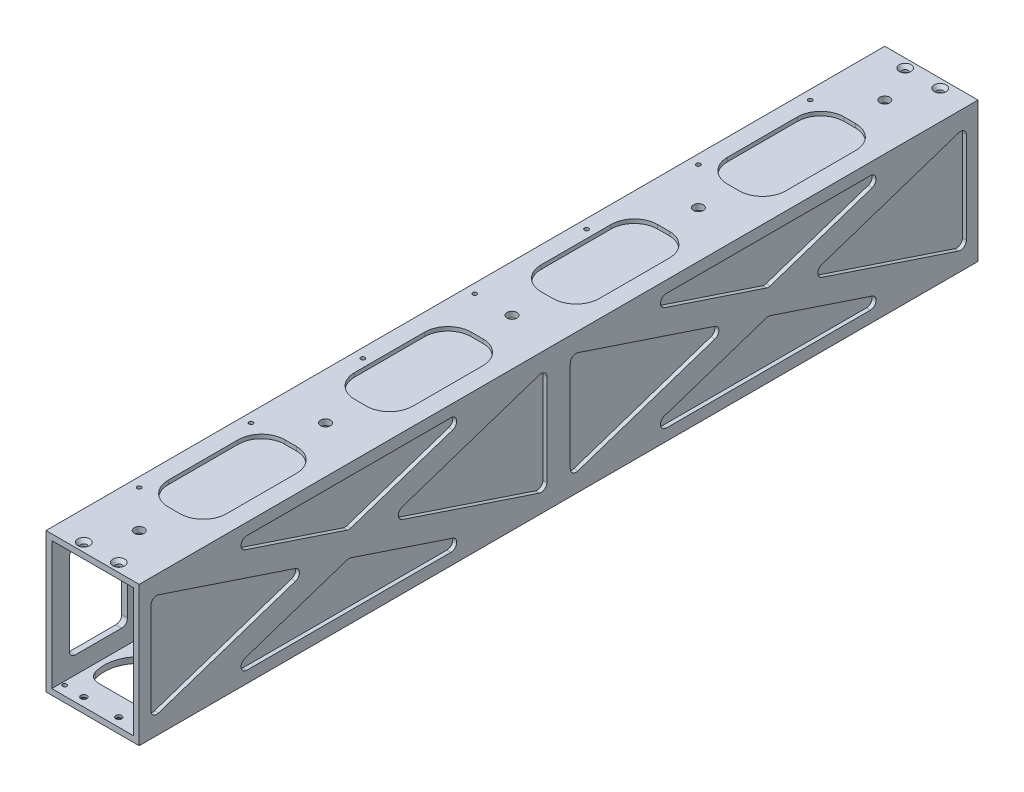
SolidWorks part; units mm, degrees
material "6061-T6 (SS)"
ref_plane "Front Plane" through (0, 0, 0) normal (0, 0, 1) x (1, 0, 0)
ref_plane "Top Plane" through (0, 0, 0) normal (0, 1, 0) x (1, 0, 0)
ref_plane "Right Plane" through (0, 0, 0) normal (1, 0, 0) x (0, 0, -1)
sketch "Sketch1" plane through (0, 0, 0) normal (0, 0, 1) x (1, 0, 0)
  line L0 (3.175, 3.175) -> (3.175, 73.025)
  line L1 (0, 0) -> (50.8, 0)
  line L2 (0, 0) -> (0, 76.2)
  line L3 (0, 76.2) -> (50.8, 76.2)
  line L4 (50.8, 0) -> (50.8, 76.2)
  line L5 (3.175, 73.025) -> (47.625, 73.025)
  line L6 (47.625, 3.175) -> (47.625, 73.025)
  line L7 (3.175, 3.175) -> (47.625, 3.175)
  dimension "D1" = 76.2
  dimension "D2" = 50.8
  dimension "D3" = 3.175
extrude "Boss-Extrude1" add sketch "Sketch1" along normal blind 457.2
sketch "Sketch2" plane through (50.8, 0, 0) normal (1, 0, 0) x (0, 0, -1)
  line L0 (-457.2, 76.2) -> (-228.6, 0) construction
  line L1 (-457.2, 0) -> (0, 0) construction
  line L2 (-228.6, 0) -> (-228.6, 76.2) construction
  line L3 (-457.2, 76.2) -> (0, 76.2) construction
  line L4 (-228.6, 76.2) -> (0, 0) construction
  line L5 (-457.2, 0) -> (-228.6, 76.2) construction
  line L6 (0, 76.2) -> (-228.6, 0) construction
  line L7 (-222.25, 62.9848) -> (-222.25, 13.2152)
  line L8 (-399.5083, 63.6629) -> (-343.904, 45.1282)
  line L9 (-459.208, 70.1759) -> (-230.608, -6.0241) construction
  line L10 (-455.192, 82.2241) -> (-226.592, 6.0241) construction
  line L11 (-446.671, 65.9968) -> (-372.0167, 41.1121)
  line L12 (-459.208, 6.0241) -> (-230.608, 82.2241) construction
  line L13 (-226.592, 82.2241) -> (2.008, 6.0241) construction
  line L14 (-455.192, -6.0241) -> (-226.592, 70.1759) construction
  line L15 (-234.95, 62.9848) -> (-234.95, 13.2152)
  line L16 (-57.6917, 63.6629) -> (-113.296, 45.1282)
  line L17 (-10.529, 65.9968) -> (-85.1833, 41.1121)
  line L18 (-170.9083, 63.6629) -> (-115.304, 45.1282)
  line L19 (-218.071, 65.9968) -> (-143.4167, 41.1121)
  line L20 (-6.35, 6.35) -> (-6.35, 69.85)
  line L21 (-6.35, 69.85) -> (-450.85, 69.85)
  line L22 (-450.85, 69.85) -> (-450.85, 6.35)
  line L23 (-450.85, 6.35) -> (-6.35, 6.35)
  line L24 (-6.35, 13.2152) -> (-6.35, 62.9848)
  line L25 (-287.2957, 69.85) -> (-398.5043, 69.85)
  line L26 (-450.85, 62.9848) -> (-450.85, 13.2152)
  line L27 (-398.5043, 6.35) -> (-287.2957, 6.35)
  line L28 (-446.671, 10.2032) -> (-372.0167, 35.0879)
  line L29 (-399.5083, 12.5371) -> (-343.904, 31.0718)
  line L30 (-341.896, 45.1282) -> (-286.2917, 63.6629)
  line L31 (-313.7833, 41.1121) -> (-239.129, 65.9968)
  line L32 (-230.608, 70.1759) -> (-2.008, -6.0241) construction
  line L33 (-341.896, 31.0718) -> (-286.2917, 12.5371)
  line L34 (2.008, 70.1759) -> (-226.592, -6.0241) construction
  line L35 (-2.008, 82.2241) -> (-230.608, 6.0241) construction
  line L36 (-313.7833, 35.0879) -> (-239.129, 10.2032)
  line L37 (-143.4167, 35.0879) -> (-218.071, 10.2032)
  line L38 (-113.296, 31.0718) -> (-57.6917, 12.5371)
  line L39 (-85.1833, 35.0879) -> (-10.529, 10.2032)
  line L40 (-115.304, 31.0718) -> (-170.9083, 12.5371)
  line L41 (-169.9043, 69.85) -> (-58.6957, 69.85)
  line L42 (-169.9043, 6.35) -> (-58.6957, 6.35)
  arc A0 (-85.1833, 35.0879) -> (-85.1833, 41.1121) centre (-84.1793, 38.1) cw
  arc A1 (-113.296, 45.1282) -> (-115.304, 45.1282) centre (-114.3, 48.1402) cw
  arc A2 (-218.071, 10.2032) -> (-222.25, 13.2152) centre (-219.075, 13.2152) cw
  arc A3 (-222.25, 62.9848) -> (-218.071, 65.9968) centre (-219.075, 62.9848) cw
  arc A4 (-287.2957, 6.35) -> (-286.2917, 12.5371) centre (-287.2957, 9.525) ccw
  arc A5 (-398.5043, 6.35) -> (-399.5083, 12.5371) centre (-398.5043, 9.525) cw
  arc A6 (-341.896, 31.0718) -> (-343.904, 31.0718) centre (-342.9, 28.0598) ccw
  arc A7 (-239.129, 10.2032) -> (-234.95, 13.2152) centre (-238.125, 13.2152) ccw
  arc A8 (-234.95, 62.9848) -> (-239.129, 65.9968) centre (-238.125, 62.9848) ccw
  arc A9 (-313.7833, 35.0879) -> (-313.7833, 41.1121) centre (-312.7793, 38.1) cw
  arc A10 (-286.2917, 63.6629) -> (-287.2957, 69.85) centre (-287.2957, 66.675) ccw
  arc A11 (-398.5043, 69.85) -> (-399.5083, 63.6629) centre (-398.5043, 66.675) ccw
  arc A12 (-341.896, 45.1282) -> (-343.904, 45.1282) centre (-342.9, 48.1402) cw
  arc A13 (-372.0167, 35.0879) -> (-372.0167, 41.1121) centre (-373.0207, 38.1) ccw
  arc A14 (-446.671, 10.2032) -> (-450.85, 13.2152) centre (-447.675, 13.2152) cw
  arc A15 (-450.85, 62.9848) -> (-446.671, 65.9968) centre (-447.675, 62.9848) cw
  arc A16 (-143.4167, 35.0879) -> (-143.4167, 41.1121) centre (-144.4207, 38.1) ccw
  arc A17 (-6.35, 62.9848) -> (-10.529, 65.9968) centre (-9.525, 62.9848) ccw
  arc A18 (-6.35, 13.2152) -> (-10.529, 10.2032) centre (-9.525, 13.2152) cw
  arc A19 (-57.6917, 12.5371) -> (-58.6957, 6.35) centre (-58.6957, 9.525) cw
  arc A20 (-169.9043, 6.35) -> (-170.9083, 12.5371) centre (-169.9043, 9.525) cw
  arc A21 (-113.296, 31.0718) -> (-115.304, 31.0718) centre (-114.3, 28.0598) ccw
  arc A22 (-57.6917, 63.6629) -> (-58.6957, 69.85) centre (-58.6957, 66.675) ccw
  arc A23 (-169.9043, 69.85) -> (-170.9083, 63.6629) centre (-169.9043, 66.675) ccw
  point P36 (-260.35, 0)
  point P37 (-260.35, 101.6)
  point P38 (-247.65, 0)
  point P39 (-247.65, 101.6)
  point P77 (-342.9, 31.4065)
  point P83 (-322.8195, 38.1)
  point P104 (-39.1305, 6.35)
  point P107 (-189.4695, 6.35)
  point P110 (-114.3, 31.4065)
  point P113 (-39.1305, 69.85)
  point P116 (-189.4695, 69.85)
  dimension "D13" = 3.175
  dimension "D14" = 3.175
  dimension "D11" = 6.35
  dimension "D12" = 6.35
  dimension "D2" = 6.35
  dimension "D3" = 6.35
  dimension "D4" = 6.35
  dimension "D5" = 6.35
  dimension "D6" = 6.35
  dimension "D7" = 6.35
  dimension "D8" = 6.35
  dimension "D9" = 6.35
  dimension "D10" = 6.35
extrude "Cut-Extrude2" cut sketch "Sketch2" against normal through all
sketch "Sketch3" plane through (0, 76.2, 0) normal (0, 1, 0) x (1, 0, 0)
  line L0 (50.8, 0) -> (0, 0) construction
  line L1 (50.8, -457.2) -> (50.8, 0) construction
  circle A0 centre (25.4, -25.4) radius 19.05
  circle A1 centre (25.4, -76.2) radius 19.05
  circle A2 centre (25.4, -127) radius 19.05
  circle A3 centre (25.4, -177.8) radius 19.05
  circle A4 centre (25.4, -228.6) radius 19.05 construction
  circle A5 centre (25.4, -279.4) radius 19.05
  circle A6 centre (25.4, -330.2) radius 19.05
  circle A7 centre (25.4, -381) radius 19.05
  circle A8 centre (25.4, -431.8) radius 19.05
  circle A9 centre (25.4, -482.6) radius 19.05
  circle A10 centre (25.4, -533.4) radius 19.05
  dimension "D1" = 38.1
  dimension "D2" = 25.4
  dimension "D4" = 25.4
  dimension "D3" = 11
extrude "Cut-Extrude3" [suppressed] cut sketch "Sketch3" against normal through all
hole_wizard "1/4-28 Tapped Hole1" positions "Sketch5" profile "Sketch4" tap size "1/4-28" standard "Ansi Inch"
sketch "Sketch5" plane through (0, 76.2, 0) normal (0, 1, 0) x (-1, 0, 0)
  line L0 (-25.4, 0) -> (-25.4, 457.2) construction
  line L1 (-50.8, 0) -> (0, 0) construction
  line L2 (-50.8, 457.2) -> (0, 457.2) construction
  point P0 (-25.4, 25.4)
  point P1 (-25.4, 228.6)
  point P2 (-25.4, 431.8)
  point P16 (-25.4, 228.6)
  point P18 (-25.4, 330.2)
  point P20 (-25.4, 127)
  dimension "D1" = 25.4
  dimension "D2" = 25.4
  dimension "D3" = 101.6
  dimension "D4" = 101.6
sketch "Sketch4" plane through (25.4, 76.2, 25.4) normal (1, 0, 0) x (0, 0, 1)
  line L0 (0, 0) -> (0, 3.175)
  line L1 (0, 3.175) -> (2.7051, 3.175)
  line L2 (2.7051, 3.175) -> (2.7051, 0)
  line L5 (2.7051, 0) -> (0, 0)
  line L11 (0, -6.35) -> (0, 107.95) construction
  dimension "Thru Tap Drill Dia." = 5.4102
  dimension "Thru Tap Drill Depth" = 3.175
cosmetic thread "Hole Thread1"
cosmetic thread "Hole Thread2"
cosmetic thread "Hole Thread3"
cosmetic thread "Hole Thread4"
cosmetic thread "Hole Thread5"
sketch "Sketch6" plane through (0, 0, 0) normal (-1, 0, 0) x (0, 0, 1)
  line L0 (457.2, 0) -> (0, 0) construction
  line L1 (0, 76.2) -> (53.975, 76.2)
  line L2 (0, 76.2) -> (0, 0)
  line L3 (0, 0) -> (53.975, 0)
  line L4 (53.975, 76.2) -> (53.975, 0)
  dimension "D1" = 53.975
extrude "Boss-Extrude2" add sketch "Sketch6" against normal up to surface (3.175 mm away) up to face at (3.175, 16.5378, 114.3)
sketch "Sketch7" plane through (0, 0, 0) normal (-1, 0, 0) x (0, 0, 1)
  line L0 (25.4, 76.2) -> (25.4, 0) construction
  line L1 (457.2, 76.2) -> (0, 76.2) construction
  line L2 (0, 76.2) -> (0, 0) construction
  line L3 (457.2, 0) -> (0, 0) construction
  line L4 (9.525, 12.7) -> (41.275, 12.7)
  line L5 (9.525, 12.7) -> (9.525, 63.5)
  line L6 (9.525, 63.5) -> (41.275, 63.5)
  line L7 (41.275, 12.7) -> (41.275, 63.5)
  line L8 (9.525, 12.7) -> (41.275, 63.5) construction
  line L9 (9.525, 63.5) -> (41.275, 12.7) construction
  point P6 (25.4, 38.1)
  dimension "D1" = 25.4
  dimension "D2" = 50.8
  dimension "D3" = 31.75
extrude "Cut-Extrude4" cut sketch "Sketch7" against normal up to next
ref_plane "Plane1" through (0, 0, 228.6) normal (0, 0, 1) x (1, 0, 0)
mirror "Mirror1" about plane through (0, 0, 228.6) normal (0, 0, 1) of "Boss-Extrude2", "Cut-Extrude4"
fillet "Fillet1" radius 3.175 12 edges at (1.5875, 51.5148, 53.975) (1.5875, 24.6852, 53.975) (1.5875, 12.7, 41.275) (1.5875, 12.7, 9.525) (1.5875, 63.5, 41.275) (1.5875, 63.5, 9.525) (1.5875, 51.5148, 403.225) (1.5875, 24.6852, 403.225) (1.5875, 12.7, 447.675) (1.5875, 12.7, 415.925) (1.5875, 63.5, 415.925) (1.5875, 63.5, 447.675)
sketch "Sketch8" [suppressed] plane through (0, 0, 0) normal (0, -1, 0) x (1, 0, 0)
  line L0 (0, 457.2) -> (0, 0) construction
  circle A0 centre (25.4, 228.6) radius 19.05
  circle A1 centre (25.4, 177.8) radius 19.05 construction
  dimension "D1" = 38.1
  dimension "D2" = 25.4
  dimension "D3" = 50.8
extrude "Cut-Extrude5" [suppressed] cut sketch "Sketch8" against normal up to next
sketch "Sketch9" plane through (0, 0, 0) normal (0, -1, 0) x (1, 0, 0)
  line L0 (0, 457.2) -> (0, 0) construction
  line L1 (0, 457.2) -> (50.8, 457.2) construction
  circle A0 centre (25.4, 431.8) radius 19.05
  circle A1 centre (25.4, 381) radius 19.05
  circle A2 centre (25.4, 330.2) radius 19.05
  circle A3 centre (25.4, 279.4) radius 19.05
  circle A4 centre (25.4, 228.6) radius 19.05
  circle A5 centre (25.4, 177.8) radius 19.05
  circle A6 centre (25.4, 127) radius 19.05
  circle A7 centre (25.4, 76.2) radius 19.05
  circle A8 centre (25.4, 25.4) radius 19.05
  dimension "D1" = 38.1
  dimension "D2" = 25.4
  dimension "D3" = 25.4
  dimension "D5" = 50.8
  dimension "D4" = 9
extrude "Cut-Extrude6" cut sketch "Sketch9" against normal up to next
sketch "Sketch10" plane through (0, 76.2, 0) normal (0, 1, 0) x (1, 0, 0)
  line L0 (0, -457.2) -> (0, 0) construction
  line L1 (28.575, -107.95) -> (22.225, -107.95)
  line L2 (41.275, -95.25) -> (41.275, -57.15)
  line L3 (28.575, -44.45) -> (22.225, -44.45)
  line L4 (9.525, -95.25) -> (9.525, -57.15)
  line L5 (41.275, -107.95) -> (9.525, -44.45) construction
  line L6 (41.275, -44.45) -> (9.525, -107.95) construction
  circle A0 centre (25.4, -25.4) radius 2.7051 construction
  arc A2 (28.575, -107.95) -> (41.275, -95.25) centre (28.575, -95.25) ccw
  arc A3 (22.225, -107.95) -> (9.525, -95.25) centre (22.225, -95.25) cw
  arc A4 (41.275, -57.15) -> (28.575, -44.45) centre (28.575, -57.15) ccw
  arc A5 (22.225, -44.45) -> (9.525, -57.15) centre (22.225, -57.15) ccw
  point P0 (25.4, -76.2)
  dimension "D5" = 12.7
  dimension "D1" = 25.4
  dimension "D2" = 31.75
  dimension "D3" = 63.5
  dimension "D4" = 50.8
extrude "Cut-Extrude7" cut sketch "Sketch10" against normal up to next
pattern_linear "LPattern1" count 4 spacing 101.6 along (0, 0, 1) of "Cut-Extrude7"
hole_wizard "CSK for #4 Flat Head Socket Cap Screw1" positions "Sketch13" profile "Sketch12" countersink size "#4" standard "Ansi Inch" end condition up to next
sketch "Sketch13" plane through (0, 76.2, 0) normal (0, 1, 0) x (-1, 0, 0)
  line L0 (0, 457.2) -> (0, 0) construction
  line L1 (-50.8, 0) -> (0, 0) construction
  point P0 (-15.875, 4.7625)
  point P1 (-34.925, 4.7625)
  dimension "D1" = 19.05
  dimension "D2" = 15.875
  dimension "D3" = 4.7625
sketch "Sketch12" plane through (15.875, 76.2, 4.7625) normal (1, 0, 0) x (0, 0, 1)
  line L0 (0, 0) -> (0, 3.176)
  line L1 (0, 3.176) -> (1.6319, 3.176)
  line L2 (1.6319, 3.176) -> (1.6319, 1.8481)
  line L3 (1.6319, 1.8481) -> (3.2385, 0)
  line L5 (3.2385, 0) -> (0, 0)
  line L6 (-1.6319, 1.8481) -> (-3.2385, 0) construction
  line L11 (0, -6.35) -> (0, 107.95) construction
  dimension "Thru Hole Dia." = 3.2639
  dimension "Thru Hole Depth" = 3.176
  dimension "Near C'Sink Dia." = 6.477
  dimension "Near C'Sink Angle" = 82
ref_plane "Plane2" through (0, 38.1, 0) normal (0, 1, 0) x (-1, 0, 0)
ref_plane "Plane3" through (0, 0, 228.6) normal (0, 0, -1) x (-1, 0, 0)
mirror "Mirror2" about plane through (0, 38.1, 0) normal (0, 1, 0) of "CSK for #4 Flat Head Socket Cap Screw1"
mirror "Mirror3" about plane through (0, 0, 228.6) normal (0, 0, -1) of "Mirror2", "CSK for #4 Flat Head Socket Cap Screw1"
sketch "Sketch15" plane through (47.625, 0, 0) normal (-1, 0, 0) x (0, 0, 1)
  line L3 (446.671, 65.9968) -> (372.0167, 41.1121)
  line L4 (450.85, 13.2152) -> (450.85, 62.9848)
  line L5 (372.0167, 35.0879) -> (446.671, 10.2032)
  line L6 (446.671, 65.9968) -> (372.0167, 41.1121)
  line L7 (450.85, 13.2152) -> (450.85, 62.9848)
  line L8 (372.0167, 35.0879) -> (446.671, 10.2032)
  line L9 (398.5043, 69.85) -> (287.2957, 69.85)
  line L10 (343.904, 45.1282) -> (399.5083, 63.6629)
  line L11 (286.2917, 63.6629) -> (341.896, 45.1282)
  line L12 (398.5043, 69.85) -> (287.2957, 69.85)
  line L13 (343.904, 45.1282) -> (399.5083, 63.6629)
  line L14 (286.2917, 63.6629) -> (341.896, 45.1282)
  line L15 (341.896, 31.0718) -> (286.2917, 12.5371)
  line L16 (399.5083, 12.5371) -> (343.904, 31.0718)
  line L17 (287.2957, 6.35) -> (398.5043, 6.35)
  line L18 (341.896, 31.0718) -> (286.2917, 12.5371)
  line L19 (399.5083, 12.5371) -> (343.904, 31.0718)
  line L20 (287.2957, 6.35) -> (398.5043, 6.35)
  line L21 (239.129, 10.2032) -> (313.7833, 35.0879)
  line L22 (234.95, 62.9848) -> (234.95, 13.2152)
  line L23 (313.7833, 41.1121) -> (239.129, 65.9968)
  line L24 (239.129, 10.2032) -> (313.7833, 35.0879)
  line L25 (234.95, 62.9848) -> (234.95, 13.2152)
  line L26 (313.7833, 41.1121) -> (239.129, 65.9968)
  line L27 (143.4167, 35.0879) -> (218.071, 10.2032)
  line L28 (218.071, 65.9968) -> (143.4167, 41.1121)
  line L29 (222.25, 13.2152) -> (222.25, 62.9848)
  line L30 (143.4167, 35.0879) -> (218.071, 10.2032)
  line L31 (218.071, 65.9968) -> (143.4167, 41.1121)
  line L32 (222.25, 13.2152) -> (222.25, 62.9848)
  line L33 (57.6917, 63.6629) -> (113.296, 45.1282)
  line L34 (169.9043, 69.85) -> (58.6957, 69.85)
  line L35 (115.304, 45.1282) -> (170.9083, 63.6629)
  line L36 (57.6917, 63.6629) -> (113.296, 45.1282)
  line L37 (169.9043, 69.85) -> (58.6957, 69.85)
  line L38 (115.304, 45.1282) -> (170.9083, 63.6629)
  line L39 (113.296, 31.0718) -> (57.6917, 12.5371)
  line L40 (170.9083, 12.5371) -> (115.304, 31.0718)
  line L41 (58.6957, 6.35) -> (169.9043, 6.35)
  line L42 (113.296, 31.0718) -> (57.6917, 12.5371)
  line L43 (170.9083, 12.5371) -> (115.304, 31.0718)
  line L44 (58.6957, 6.35) -> (169.9043, 6.35)
  line L45 (10.529, 10.2032) -> (85.1833, 35.0879)
  line L46 (6.35, 62.9848) -> (6.35, 13.2152)
  line L47 (85.1833, 41.1121) -> (10.529, 65.9968)
  line L48 (10.529, 10.2032) -> (85.1833, 35.0879)
  line L49 (6.35, 62.9848) -> (6.35, 13.2152)
  line L50 (85.1833, 41.1121) -> (10.529, 65.9968)
  arc A3 (372.0167, 41.1121) -> (372.0167, 35.0879) centre (373.0207, 38.1) ccw
  arc A4 (450.85, 62.9848) -> (446.671, 65.9968) centre (447.675, 62.9848) ccw
  arc A5 (446.671, 10.2032) -> (450.85, 13.2152) centre (447.675, 13.2152) ccw
  arc A6 (372.0167, 41.1121) -> (372.0167, 35.0879) centre (373.0207, 38.1) ccw
  arc A7 (450.85, 62.9848) -> (446.671, 65.9968) centre (447.675, 62.9848) ccw
  arc A8 (446.671, 10.2032) -> (450.85, 13.2152) centre (447.675, 13.2152) ccw
  arc A9 (287.2957, 69.85) -> (286.2917, 63.6629) centre (287.2957, 66.675) ccw
  arc A10 (399.5083, 63.6629) -> (398.5043, 69.85) centre (398.5043, 66.675) ccw
  arc A11 (341.896, 45.1282) -> (343.904, 45.1282) centre (342.9, 48.1402) ccw
  arc A12 (287.2957, 69.85) -> (286.2917, 63.6629) centre (287.2957, 66.675) ccw
  arc A13 (399.5083, 63.6629) -> (398.5043, 69.85) centre (398.5043, 66.675) ccw
  arc A14 (341.896, 45.1282) -> (343.904, 45.1282) centre (342.9, 48.1402) ccw
  arc A15 (286.2917, 12.5371) -> (287.2957, 6.35) centre (287.2957, 9.525) ccw
  arc A16 (343.904, 31.0718) -> (341.896, 31.0718) centre (342.9, 28.0598) ccw
  arc A17 (398.5043, 6.35) -> (399.5083, 12.5371) centre (398.5043, 9.525) ccw
  arc A18 (286.2917, 12.5371) -> (287.2957, 6.35) centre (287.2957, 9.525) ccw
  arc A19 (343.904, 31.0718) -> (341.896, 31.0718) centre (342.9, 28.0598) ccw
  arc A20 (398.5043, 6.35) -> (399.5083, 12.5371) centre (398.5043, 9.525) ccw
  arc A21 (313.7833, 35.0879) -> (313.7833, 41.1121) centre (312.7793, 38.1) ccw
  arc A22 (234.95, 13.2152) -> (239.129, 10.2032) centre (238.125, 13.2152) ccw
  arc A23 (239.129, 65.9968) -> (234.95, 62.9848) centre (238.125, 62.9848) ccw
  arc A24 (313.7833, 35.0879) -> (313.7833, 41.1121) centre (312.7793, 38.1) ccw
  arc A25 (234.95, 13.2152) -> (239.129, 10.2032) centre (238.125, 13.2152) ccw
  arc A26 (239.129, 65.9968) -> (234.95, 62.9848) centre (238.125, 62.9848) ccw
  arc A27 (218.071, 10.2032) -> (222.25, 13.2152) centre (219.075, 13.2152) ccw
  arc A28 (143.4167, 41.1121) -> (143.4167, 35.0879) centre (144.4207, 38.1) ccw
  arc A29 (222.25, 62.9848) -> (218.071, 65.9968) centre (219.075, 62.9848) ccw
  arc A30 (218.071, 10.2032) -> (222.25, 13.2152) centre (219.075, 13.2152) ccw
  arc A31 (143.4167, 41.1121) -> (143.4167, 35.0879) centre (144.4207, 38.1) ccw
  arc A32 (222.25, 62.9848) -> (218.071, 65.9968) centre (219.075, 62.9848) ccw
  arc A33 (113.296, 45.1282) -> (115.304, 45.1282) centre (114.3, 48.1402) ccw
  arc A34 (58.6957, 69.85) -> (57.6917, 63.6629) centre (58.6957, 66.675) ccw
  arc A35 (170.9083, 63.6629) -> (169.9043, 69.85) centre (169.9043, 66.675) ccw
  arc A36 (113.296, 45.1282) -> (115.304, 45.1282) centre (114.3, 48.1402) ccw
  arc A37 (58.6957, 69.85) -> (57.6917, 63.6629) centre (58.6957, 66.675) ccw
  arc A38 (170.9083, 63.6629) -> (169.9043, 69.85) centre (169.9043, 66.675) ccw
  arc A39 (57.6917, 12.5371) -> (58.6957, 6.35) centre (58.6957, 9.525) ccw
  arc A40 (115.304, 31.0718) -> (113.296, 31.0718) centre (114.3, 28.0598) ccw
  arc A41 (169.9043, 6.35) -> (170.9083, 12.5371) centre (169.9043, 9.525) ccw
  arc A42 (57.6917, 12.5371) -> (58.6957, 6.35) centre (58.6957, 9.525) ccw
  arc A43 (115.304, 31.0718) -> (113.296, 31.0718) centre (114.3, 28.0598) ccw
  arc A44 (169.9043, 6.35) -> (170.9083, 12.5371) centre (169.9043, 9.525) ccw
  arc A45 (85.1833, 35.0879) -> (85.1833, 41.1121) centre (84.1793, 38.1) ccw
  arc A46 (6.35, 13.2152) -> (10.529, 10.2032) centre (9.525, 13.2152) ccw
  arc A47 (10.529, 65.9968) -> (6.35, 62.9848) centre (9.525, 62.9848) ccw
  arc A48 (85.1833, 35.0879) -> (85.1833, 41.1121) centre (84.1793, 38.1) ccw
  arc A49 (6.35, 13.2152) -> (10.529, 10.2032) centre (9.525, 13.2152) ccw
  arc A50 (10.529, 65.9968) -> (6.35, 62.9848) centre (9.525, 62.9848) ccw
  dimension "D1" = 0
  dimension "D2" = 0
  dimension "D3" = 0
  dimension "D4" = 0
  dimension "D5" = 0
  dimension "D6" = 0
  dimension "D7" = 0
  dimension "D8" = 0
extrude "Boss-Extrude3" add sketch "Sketch15" against normal blind 1.016
sketch "Sketch16" plane through (0, 3.175, 0) normal (0, 1, 0) x (1, 0, 0)
  circle A1 centre (25.4, -431.8) radius 19.05
  circle A2 centre (25.4, -431.8) radius 19.05
  circle A3 centre (25.4, -25.4) radius 19.05
  circle A4 centre (25.4, -25.4) radius 19.05
  dimension "D1" = 0
  dimension "D2" = 0
extrude "Boss-Extrude4" add sketch "Sketch16" against normal blind 1.016
sketch "Sketch17" plane through (0, 73.025, 0) normal (0, -1, 0) x (1, 0, 0)
  line L4 (41.275, 57.15) -> (41.275, 95.25)
  line L5 (22.225, 44.45) -> (28.575, 44.45)
  line L6 (9.525, 95.25) -> (9.525, 57.15)
  line L7 (28.575, 107.95) -> (22.225, 107.95)
  line L8 (41.275, 57.15) -> (41.275, 95.25)
  line L9 (22.225, 44.45) -> (28.575, 44.45)
  line L10 (9.525, 95.25) -> (9.525, 57.15)
  line L11 (28.575, 107.95) -> (22.225, 107.95)
  line L12 (41.275, 158.75) -> (41.275, 196.85)
  line L13 (22.225, 146.05) -> (28.575, 146.05)
  line L14 (9.525, 196.85) -> (9.525, 158.75)
  line L15 (28.575, 209.55) -> (22.225, 209.55)
  line L16 (41.275, 158.75) -> (41.275, 196.85)
  line L17 (22.225, 146.05) -> (28.575, 146.05)
  line L18 (9.525, 196.85) -> (9.525, 158.75)
  line L19 (28.575, 209.55) -> (22.225, 209.55)
  line L20 (41.275, 260.35) -> (41.275, 298.45)
  line L21 (22.225, 247.65) -> (28.575, 247.65)
  line L22 (9.525, 298.45) -> (9.525, 260.35)
  line L23 (28.575, 311.15) -> (22.225, 311.15)
  line L24 (41.275, 260.35) -> (41.275, 298.45)
  line L25 (22.225, 247.65) -> (28.575, 247.65)
  line L26 (9.525, 298.45) -> (9.525, 260.35)
  line L27 (28.575, 311.15) -> (22.225, 311.15)
  line L28 (41.275, 361.95) -> (41.275, 400.05)
  line L29 (22.225, 349.25) -> (28.575, 349.25)
  line L30 (9.525, 400.05) -> (9.525, 361.95)
  line L31 (28.575, 412.75) -> (22.225, 412.75)
  line L32 (41.275, 361.95) -> (41.275, 400.05)
  line L33 (22.225, 349.25) -> (28.575, 349.25)
  line L34 (9.525, 400.05) -> (9.525, 361.95)
  line L35 (28.575, 412.75) -> (22.225, 412.75)
  arc A4 (41.275, 95.25) -> (28.575, 107.95) centre (28.575, 95.25) ccw
  arc A5 (28.575, 44.45) -> (41.275, 57.15) centre (28.575, 57.15) ccw
  arc A6 (9.525, 57.15) -> (22.225, 44.45) centre (22.225, 57.15) ccw
  arc A7 (22.225, 107.95) -> (9.525, 95.25) centre (22.225, 95.25) ccw
  arc A8 (41.275, 95.25) -> (28.575, 107.95) centre (28.575, 95.25) ccw
  arc A9 (28.575, 44.45) -> (41.275, 57.15) centre (28.575, 57.15) ccw
  arc A10 (9.525, 57.15) -> (22.225, 44.45) centre (22.225, 57.15) ccw
  arc A11 (22.225, 107.95) -> (9.525, 95.25) centre (22.225, 95.25) ccw
  arc A12 (41.275, 196.85) -> (28.575, 209.55) centre (28.575, 196.85) ccw
  arc A13 (28.575, 146.05) -> (41.275, 158.75) centre (28.575, 158.75) ccw
  arc A14 (9.525, 158.75) -> (22.225, 146.05) centre (22.225, 158.75) ccw
  arc A15 (22.225, 209.55) -> (9.525, 196.85) centre (22.225, 196.85) ccw
  arc A16 (41.275, 196.85) -> (28.575, 209.55) centre (28.575, 196.85) ccw
  arc A17 (28.575, 146.05) -> (41.275, 158.75) centre (28.575, 158.75) ccw
  arc A18 (9.525, 158.75) -> (22.225, 146.05) centre (22.225, 158.75) ccw
  arc A19 (22.225, 209.55) -> (9.525, 196.85) centre (22.225, 196.85) ccw
  arc A20 (41.275, 298.45) -> (28.575, 311.15) centre (28.575, 298.45) ccw
  arc A21 (28.575, 247.65) -> (41.275, 260.35) centre (28.575, 260.35) ccw
  arc A22 (9.525, 260.35) -> (22.225, 247.65) centre (22.225, 260.35) ccw
  arc A23 (22.225, 311.15) -> (9.525, 298.45) centre (22.225, 298.45) ccw
  arc A24 (41.275, 298.45) -> (28.575, 311.15) centre (28.575, 298.45) ccw
  arc A25 (28.575, 247.65) -> (41.275, 260.35) centre (28.575, 260.35) ccw
  arc A26 (9.525, 260.35) -> (22.225, 247.65) centre (22.225, 260.35) ccw
  arc A27 (22.225, 311.15) -> (9.525, 298.45) centre (22.225, 298.45) ccw
  arc A28 (41.275, 400.05) -> (28.575, 412.75) centre (28.575, 400.05) ccw
  arc A29 (28.575, 349.25) -> (41.275, 361.95) centre (28.575, 361.95) ccw
  arc A30 (9.525, 361.95) -> (22.225, 349.25) centre (22.225, 361.95) ccw
  arc A31 (22.225, 412.75) -> (9.525, 400.05) centre (22.225, 400.05) ccw
  arc A32 (41.275, 400.05) -> (28.575, 412.75) centre (28.575, 400.05) ccw
  arc A33 (28.575, 349.25) -> (41.275, 361.95) centre (28.575, 361.95) ccw
  arc A34 (9.525, 361.95) -> (22.225, 349.25) centre (22.225, 361.95) ccw
  arc A35 (22.225, 412.75) -> (9.525, 400.05) centre (22.225, 400.05) ccw
  dimension "D1" = 0
  dimension "D2" = 0
  dimension "D3" = 0
  dimension "D4" = 0
extrude "Boss-Extrude5" add sketch "Sketch17" against normal blind 1.016
hole_wizard "#4-40 Tapped Hole1" positions "Sketch19" profile "Sketch20" tap size "#4-40" standard "Ansi Inch"
sketch "Sketch19" plane through (0, 0, 0) normal (0, -1, 0) x (1, 0, 0)
  line L0 (0, 457.2) -> (50.8, 457.2) construction
  line L1 (0, 457.2) -> (0, 0) construction
  line L2 (50.8, 457.2) -> (50.8, 0) construction
  line L3 (0, 0) -> (50.8, 0) construction
  point P0 (45.72, 444.5)
  point P1 (5.08, 452.12)
  point P16 (45.72, 406.4)
  point P37 (45.72, 355.6)
  point P38 (45.72, 304.8)
  point P39 (45.72, 254)
  point P40 (45.72, 203.2)
  point P41 (45.72, 152.4)
  point P42 (45.72, 101.6)
  point P43 (45.72, 50.8)
  point P44 (45.72, 12.7)
  point P49 (5.08, 5.08)
  dimension "D1" = 5.08
  dimension "D2" = 5.08
  dimension "D3" = 5.08
  dimension "D4" = 12.7
  dimension "D5" = 38.1
  dimension "D7" = 50.8
  dimension "D8" = 38.1
  dimension "D9" = 5.08
  dimension "D10" = 5.08
  dimension "D6" = 8
sketch "Sketch20" plane through (45.72, 0, 444.5) normal (1, 0, 0) x (0, 0, -1)
  line L0 (0, 0) -> (0, 3.175)
  line L1 (0, 3.175) -> (1.1303, 3.175)
  line L2 (1.1303, 3.175) -> (1.1303, 0)
  line L5 (1.1303, 0) -> (0, 0)
  line L11 (0, -6.35) -> (0, 107.95) construction
  dimension "Thread Major Dia." = 2.2606
  dimension "Thru Tap Drill Depth" = 3.175
sketch "Sketch21" plane through (0, 2.159, 0) normal (0, -1, 0) x (1, 0, 0)
  line L0 (9.2855, 441.96) -> (41.5145, 441.96)
  line L1 (0, 457.2) -> (50.8, 457.2) construction
  line L2 (9.2855, 15.24) -> (41.5145, 15.24)
  line L3 (0, 0) -> (50.8, 0) construction
  circle A0 centre (25.4, 431.8) radius 19.05 construction
  arc A1 (41.5145, 441.96) -> (9.2855, 441.96) centre (25.4, 431.8) ccw
  circle A2 centre (25.4, 25.4) radius 19.05 construction
  arc A3 (9.2855, 15.24) -> (41.5145, 15.24) centre (25.4, 25.4) ccw
  dimension "D1" = 15.24
  dimension "D2" = 15.24
extrude "Boss-Extrude6" add sketch "Sketch21" along normal up to surface (2.159 mm away) up to face at (5.08, 0, 450.9897)
fillet "Fillet2" radius 6.35 4 edges at (9.2855, 1.0795, 441.96) (41.5145, 1.0795, 441.96) (9.2855, 1.0795, 15.24) (41.5145, 1.0795, 15.24)
sketch "Sketch22" plane through (0, 2.159, 0) normal (0, -1, 0) x (1, 0, 0)
  line L1 (13.285, 15.24) -> (37.515, 15.24)
  line L2 (13.285, 15.24) -> (37.515, 15.24)
  line L3 (37.515, 441.96) -> (13.285, 441.96)
  line L4 (37.515, 441.96) -> (13.285, 441.96)
  arc A3 (37.515, 15.24) -> (43.5725, 19.685) centre (37.515, 21.59) ccw
  arc A4 (43.5725, 19.685) -> (7.2275, 19.685) centre (25.4, 25.4) ccw
  arc A5 (7.2275, 19.685) -> (13.285, 15.24) centre (13.285, 21.59) ccw
  arc A6 (37.515, 15.24) -> (43.5725, 19.685) centre (37.515, 21.59) ccw
  arc A7 (43.5725, 19.685) -> (7.2275, 19.685) centre (25.4, 25.4) ccw
  arc A8 (7.2275, 19.685) -> (13.285, 15.24) centre (13.285, 21.59) ccw
  arc A9 (7.2275, 437.515) -> (43.5725, 437.515) centre (25.4, 431.8) ccw
  arc A10 (43.5725, 437.515) -> (37.515, 441.96) centre (37.515, 435.61) ccw
  arc A11 (13.285, 441.96) -> (7.2275, 437.515) centre (13.285, 435.61) ccw
  arc A12 (7.2275, 437.515) -> (43.5725, 437.515) centre (25.4, 431.8) ccw
  arc A13 (43.5725, 437.515) -> (37.515, 441.96) centre (37.515, 435.61) ccw
  arc A14 (13.285, 441.96) -> (7.2275, 437.515) centre (13.285, 435.61) ccw
  dimension "D1" = 0
  dimension "D2" = 0
extrude "Cut-Extrude8" cut sketch "Sketch22" against normal up to next
hole_wizard "#4-40 Tapped Hole2" positions "Sketch26" profile "Sketch27" tap size "#4-40" standard "Ansi Inch"
sketch "Sketch26" plane through (0, 76.2, 0) normal (0, 1, 0) x (-1, 0, 0)
  line L0 (0, 457.2) -> (0, 0) construction
  line L1 (-50.8, 0) -> (0, 0) construction
  point P0 (-5.08, 45.72)
  point P11 (-5.08, 106.68)
  point P12 (-5.08, 167.64)
  point P13 (-5.08, 228.6)
  point P14 (-5.08, 289.56)
  point P15 (-5.08, 350.52)
  point P16 (-5.08, 411.48)
  dimension "D1" = 5.08
  dimension "D2" = 45.72
  dimension "D4" = 60.96
  dimension "D3" = 7
sketch "Sketch27" plane through (5.08, 76.2, 45.72) normal (1, 0, 0) x (0, 0, 1)
  line L0 (0, 0) -> (0, 3.175)
  line L1 (0, 3.175) -> (1.1303, 3.175)
  line L2 (1.1303, 3.175) -> (1.1303, 0)
  line L5 (1.1303, 0) -> (0, 0)
  line L11 (0, -6.35) -> (0, 107.95) construction
  dimension "Thread Major Dia." = 2.2606
  dimension "Thru Tap Drill Depth" = 3.175
